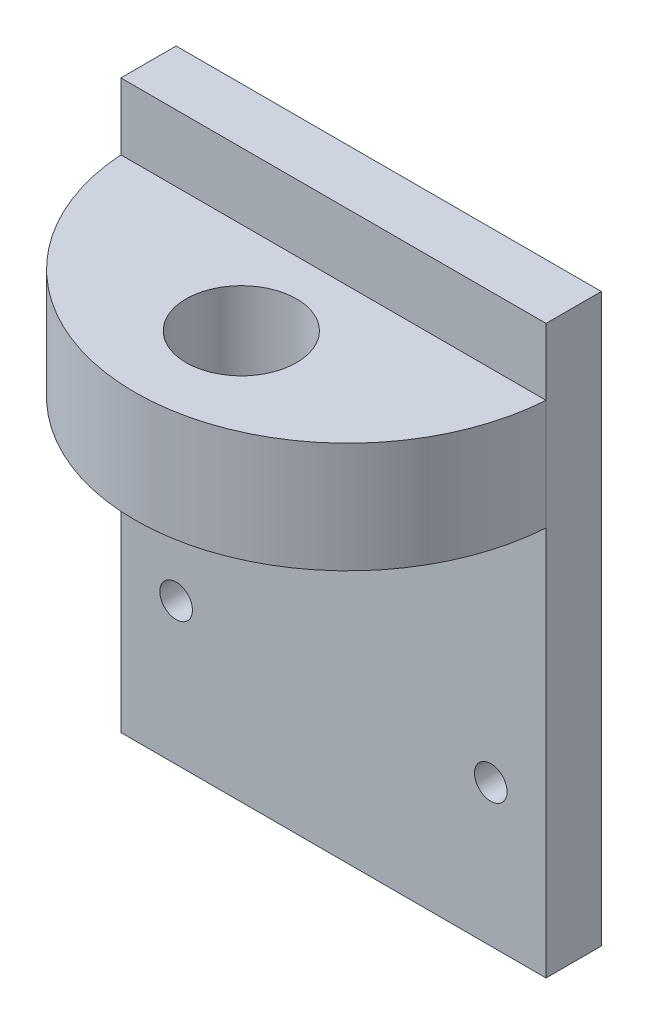
SolidWorks part; units mm, degrees
other "Markup1"
sketch "Sketch3" plane through (-76.2, 31.75, -9.906) normal (0, 1, 0) x (1, 0, 0)
other "Markup2"
sketch "Sketch4" plane through (-76.2, 31.75, -9.906) normal (-0.0008, 1, -0.0028) x (-0.9616, 0, 0.2743)
ref_plane "Front Plane" through (0, 0, 0) normal (0, 0, 1) x (1, 0, 0)
ref_plane "Top Plane" through (0, 0, 0) normal (0, 1, 0) x (1, 0, 0)
ref_plane "Right Plane" through (0, 0, 0) normal (1, 0, 0) x (0, 0, -1)
sketch "Sketch1" plane through (0, 0, 0) normal (0, 1, 0) x (1, 0, 0)
  line L0 (0, 0) -> (-76.2, 0)
  line L1 (-38.1, 2.5838) -> (-38.1, -35.6038)
  arc A0 (0, 0) -> (-76.2, 0) centre (-38.1, 2.5838) cw
  circle A1 centre (-38.1, -16.51) radius 9.906
extrude "Boss-Extrude1" add sketch "Sketch1" along normal blind 19.812 contours A1 L1 L0 A0 | A1 L1 A0 L0
sketch "Sketch2" plane through (0, 0, 0) normal (0, 0, -1) x (-1, 0, 0)
  line L0 (38.1, 19.812) -> (38.1, 0)
  line L1 (0, 19.812) -> (76.2, 19.812) construction
  line L2 (0, 0) -> (76.2, 0) construction
  line L3 (0, 0) -> (0, -69.85)
  line L8 (76.2, 0) -> (76.2, -69.85)
  line L9 (0, -69.85) -> (76.2, -69.85)
  line L10 (0, 0) -> (0, 31.75)
  line L11 (0, 31.75) -> (76.2, 31.75)
  line L12 (76.2, 31.75) -> (76.2, 0)
  circle A0 centre (9.906, -44.45) radius 2.921
  circle A1 centre (66.294, -44.45) radius 2.921
  point P6 (38.1, 9.906)
  line M1 (0, 0) -> (76.2, 0)
  line M2 (76.2, 0) -> (76.2, 19.812)
  line M3 (76.2, 19.812) -> (0, 19.812)
  line M4 (0, 19.812) -> (0, 0)
extrude "Boss-Extrude2" add sketch "Sketch2" along normal blind 9.906 contours L3 L9 L8 M1 | L12 L11 L10 M3 | L0 M3 M1 M2 | L0 M3 M4 M1
